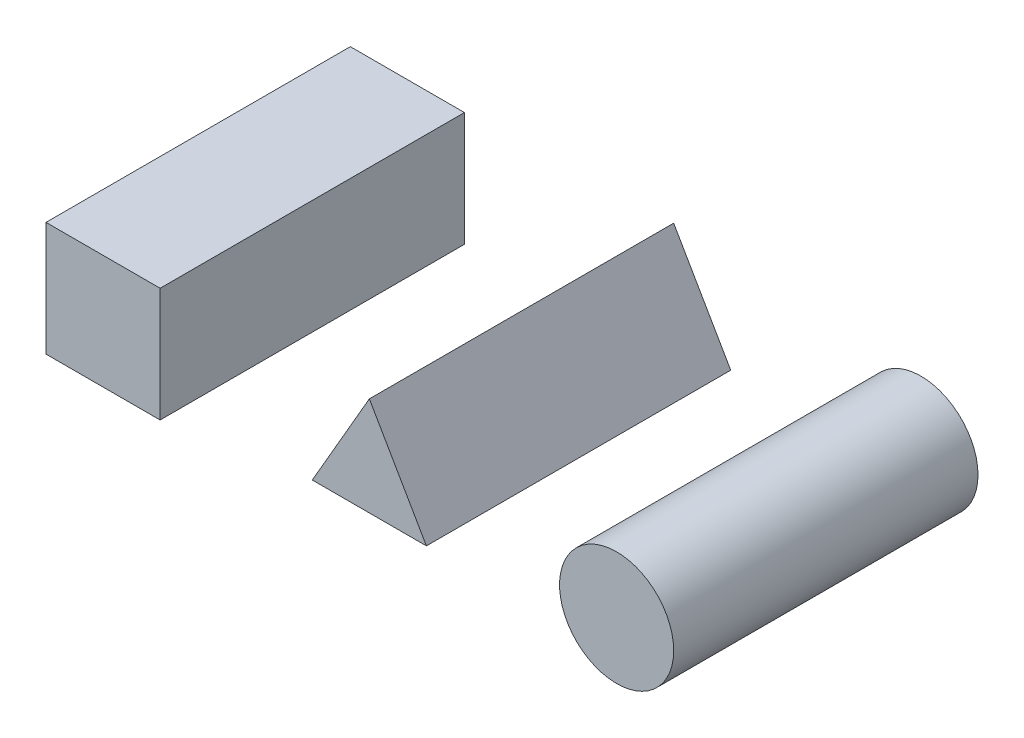
SolidWorks part; units mm, degrees
ref_plane "Front Plane" through (0, 0, 0) normal (0, 0, 1) x (1, 0, 0)
ref_plane "Top Plane" through (0, 0, 0) normal (0, 1, 0) x (1, 0, 0)
ref_plane "Right Plane" through (0, 0, 0) normal (1, 0, 0) x (0, 0, -1)
sketch "Sketch1" plane through (0, 0, 0) normal (0, 0, 1) x (1, 0, 0)
  line L0 (-115, 0) -> (115, 0) construction
  line L1 (-115, 52.5) -> (115, 52.5)
  line L2 (-115, 52.5) -> (-115, -52.5)
  line L3 (-115, -52.5) -> (115, -52.5)
  line L4 (115, 52.5) -> (115, -52.5)
  line L5 (0, 52.5) -> (0, -52.5) construction
  line L6 (-15, -8.6603) -> (0, 17.3205)
  line L7 (-85, 15) -> (-55, 15)
  line L8 (-85, 15) -> (-85, -15)
  line L9 (-85, -15) -> (-55, -15)
  line L10 (-55, 15) -> (-55, -15)
  line L11 (-85, 15) -> (-55, -15) construction
  line L12 (-85, -15) -> (-55, 15) construction
  line L14 (-1.3522, 0) -> (0, -1.3522)
  line L18 (0, 17.3205) -> (15, -8.6603)
  line L19 (15, -8.6603) -> (-15, -8.6603)
  line L20 (-15, -8.6603) -> (7.5, 4.3301) construction
  line L21 (15, -8.6603) -> (-7.5, 4.3301) construction
  line L22 (0, 17.3205) -> (0, 0) construction
  circle A0 centre (65, 0) radius 15
  point P10 (-70, 0)
  point P20 (0, 0)
  point P27 (7.7505, -5.3087)
  point P28 (0, 0)
  dimension "D2" = 50
  dimension "cylinder" = 30
  dimension "D1" = 30
  dimension "square2" = 30
  dimension "square" = 30
  dimension "triangle3" = 30
  dimension "triangle2" = 30
  dimension "triangle" = 30
extrude "Boss-Extrude1" add sketch "Sketch1" along normal blind 80
